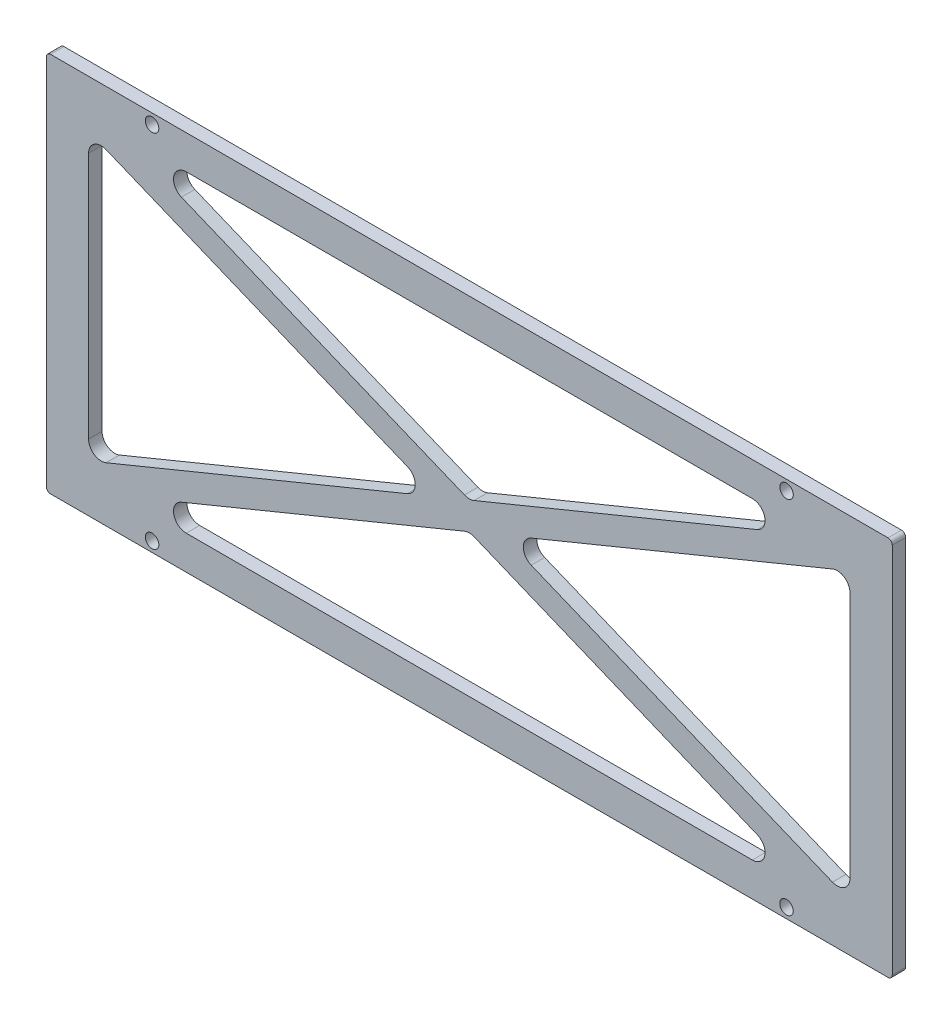
SolidWorks part; units mm, degrees
material "6061 Alloy"
ref_plane "Front Plane" through (0, 0, 0) normal (0, 0, 1) x (1, 0, 0)
ref_plane "Top Plane" through (0, 0, 0) normal (0, 1, 0) x (1, 0, 0)
ref_plane "Right Plane" through (0, 0, 0) normal (1, 0, 0) x (0, 0, -1)
sketch "Sketch1" plane through (0, 0, 0) normal (0, 0, 1) x (1, 0, 0)
  line L1 (-100, -45) -> (100, -45)
  line L2 (-100, -45) -> (-100, 45)
  line L3 (-100, 45) -> (100, 45)
  line L4 (100, -45) -> (100, 45)
  line L5 (-100, -45) -> (100, 45) construction
  line L6 (-100, 45) -> (100, -45) construction
  point P0 (0, 0)
  dimension "D1" = 90
  dimension "D2" = 200
extrude "Boss-Extrude1" add sketch "Sketch1" along normal blind 3.175
sketch "Sketch2" plane through (0, 0, 3.175) normal (0, 0, 1) x (1, 0, 0)
  line L0 (-100, -45) -> (100, -45) construction
  line L1 (-90, -37) -> (90, -37) construction
  line L2 (-90, -37) -> (-90, 37) construction
  line L3 (-90, 37) -> (90, 37) construction
  line L4 (90, -37) -> (90, 37) construction
  line L5 (-90, -37) -> (90, 37) construction
  line L6 (-90, 37) -> (90, -37) construction
  line L8 (100, 45) -> (-100, 45) construction
  line L9 (-91.1407, 34.2253) -> (88.8593, -39.7747) construction
  line L10 (-88.8593, -39.7747) -> (91.1407, 34.2253) construction
  line L11 (-88.8593, 39.7747) -> (91.1407, -34.2253) construction
  line L12 (-91.1407, -34.2253) -> (88.8593, 39.7747) construction
  line L13 (-90, 33.7564) -> (-90, -33.7564)
  line L14 (-90, -33.7564) -> (-7.8899, 0)
  line L15 (-7.8899, 0) -> (-90, 33.7564)
  line L16 (-82.1101, 37) -> (0, 3.2436)
  line L17 (0, 3.2436) -> (82.1101, 37)
  line L18 (82.1101, 37) -> (-82.1101, 37)
  line L19 (90, 33.7564) -> (7.8899, 0)
  line L20 (7.8899, 0) -> (90, -33.7564)
  line L21 (90, -33.7564) -> (90, 33.7564)
  line L22 (-82.1101, -37) -> (0, -3.2436)
  line L23 (0, -3.2436) -> (82.1101, -37)
  line L24 (82.1101, -37) -> (-82.1101, -37)
  point P0 (0, 0)
  dimension "D1" = 8
  dimension "D2" = 8
  dimension "D3" = 180
  dimension "D4" = 3
  dimension "D5" = 3
extrude "Cut-Extrude1" cut sketch "Sketch2" against normal through all
sketch "Sketch3" plane through (0, 0, 3.175) normal (0, 0, 1) x (1, 0, 0)
  line L0 (100, 45) -> (-100, 45) construction
  line L1 (-75, -42.6187) -> (75, -42.6187) construction
  line L2 (-75, -42.6187) -> (-75, 42.6188) construction
  line L3 (-75, 42.6188) -> (75, 42.6188) construction
  line L4 (75, -42.6187) -> (75, 42.6188) construction
  line L5 (-75, -42.6187) -> (75, 42.6188) construction
  line L6 (-75, 42.6188) -> (75, -42.6187) construction
  point P0 (0, 0)
  dimension "D1" = 150
  dimension "D2" = 2.3813
hole_wizard "M3 Clearance Hole1" positions "Sketch4" profile "Sketch5" hole size "M3" standard "ANSI Metric" end condition through all
sketch "Sketch4" plane through (0, 0, 3.175) normal (0, 0, 1) x (1, 0, 0)
  point P0 (-75, 42.6188)
  point P3 (75, 42.6188)
  point P6 (75, -42.6187)
  point P9 (-75, -42.6187)
sketch "Sketch5" plane through (-75, 42.6188, 3.175) normal (1, 0, 0) x (0, -1, 0)
  line L0 (0, 0) -> (0, 3.175)
  line L1 (0, 3.175) -> (1.6, 3.175)
  line L2 (1.6, 3.175) -> (1.6, 0)
  line L5 (1.6, 0) -> (0, 0)
  line L11 (0, -6.35) -> (0, 107.95) construction
  dimension "Thru Hole Dia." = 3.2
  dimension "Thru Hole Depth" = 3.175
fillet "Fillet1" radius 3 12 edges at (90, -33.7564, 1.5875) (90, 33.7564, 1.5875) (7.8899, 0, 1.5875) (82.1101, 37, 1.5875) (-82.1101, 37, 1.5875) (0, 3.2436, 1.5875) (-7.8899, 0, 1.5875) (-90, 33.7564, 1.5875) (-90, -33.7564, 1.5875) (0, -3.2436, 1.5875) (82.1101, -37, 1.5875) (-82.1101, -37, 1.5875)
fillet "Fillet2" radius 1 4 edges at (-100, -45, 1.5875) (-100, 45, 1.5875) (100, -45, 1.5875) (100, 45, 1.5875)
